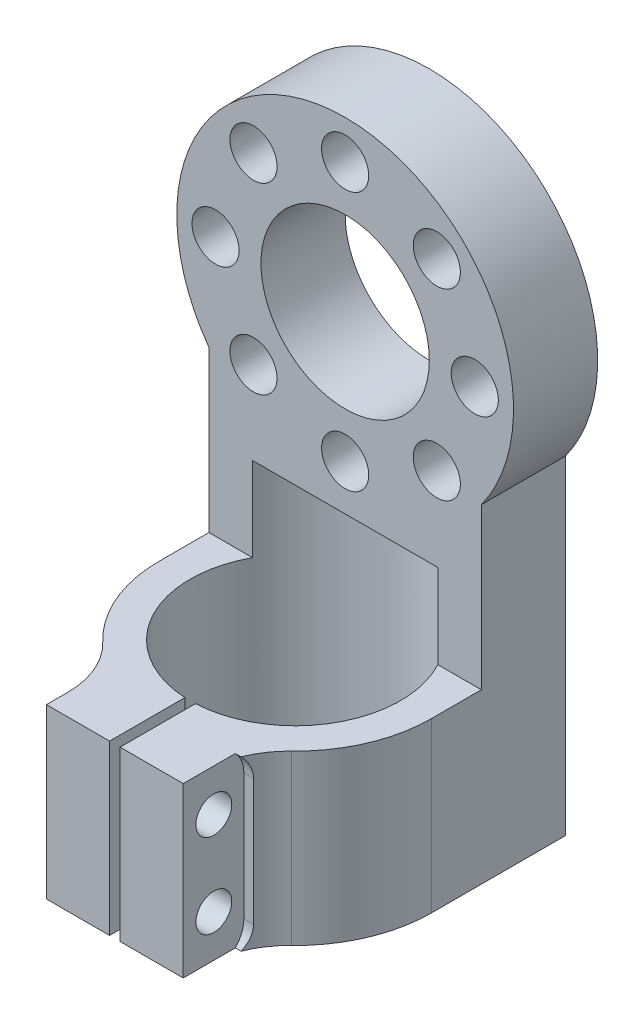
SolidWorks part; units mm, degrees
material "6061-T6 (SS)"
ref_plane "Plan de face" through (0, 0, 0) normal (0, 0, 1) x (1, 0, 0)
ref_plane "Plan de dessus" through (0, 0, 0) normal (0, 1, 0) x (1, 0, 0)
ref_plane "Plan de droite" through (0, 0, 0) normal (1, 0, 0) x (0, 0, -1)
sketch "Esquisse1" plane through (0, 0, 0) normal (0, 0, 1) x (1, 0, 0)
  line L0 (-10.2743, -7.4652) -> (-10.2743, -32.258)
  line L1 (-10.2743, -32.258) -> (10.2743, -32.258)
  line L2 (10.2743, -32.258) -> (10.2743, -7.4652)
  line L3 (0, 9.779) -> (0, 0) construction
  arc A0 (10.2743, -7.4652) -> (-10.2743, -7.4652) centre (0, 0) ccw
  circle A1 centre (0, 0) radius 6.35
  circle A2 centre (0, 9.779) radius 1.778
  circle A3 centre (0, 0) radius 9.779 construction
  circle A4 centre (6.9148, 6.9148) radius 1.778
  circle A5 centre (9.779, 0) radius 1.778
  circle A6 centre (6.9148, -6.9148) radius 1.778
  circle A7 centre (0, -9.779) radius 1.778
  circle A8 centre (-6.9148, -6.9148) radius 1.778
  circle A9 centre (-9.779, 0) radius 1.778
  circle A10 centre (-6.9148, 6.9148) radius 1.778
  point P27 (0, 0)
  dimension "D1" = 25.4
  dimension "D4" = 12.7
  dimension "D5" = 3.556
  dimension "D6" = 19.558
  dimension "D2" = 32.258
  dimension "D3" = 20.5486
  dimension "D7" = 8
extrude "Boss.-Extru.1" add sketch "Esquisse1" along normal blind 6.35
sketch "Esquisse2" plane through (0, -32.258, 0) normal (0, -1, 0) x (1, 0, 0)
  line L0 (0, 0) -> (0, 10.1092) construction
  line L1 (-10.2743, 0) -> (10.2743, 0) construction
  line L2 (-10.2743, 10.1092) -> (-10.2743, 6.35)
  line L3 (-10.2743, 6.35) -> (10.2743, 6.35)
  line L4 (10.2743, 6.35) -> (10.2743, 10.1092)
  line L5 (-5.1594, 18.9941) -> (-5.1594, 23.7236)
  line L6 (-5.1594, 23.7236) -> (5.1594, 23.7236)
  line L7 (5.1594, 23.7236) -> (5.1594, 18.9941)
  line L8 (0, 23.7236) -> (0, 10.1092) construction
  arc A0 (10.2743, 10.1092) -> (5.1594, 18.9941) centre (0, 10.1092) ccw
  arc A1 (-5.1594, 18.9941) -> (-10.2743, 10.1092) centre (0, 10.1092) ccw
  dimension "D1" = 10.1092
  dimension "D2" = 23.7236
  dimension "D3" = 10.3187
extrude "Boss.-Extru.2" add sketch "Esquisse2" against normal blind 12.7
sketch "Esquisse3" plane through (0, -32.258, 0) normal (0, -1, 0) x (1, 0, 0)
  line L0 (-0.3969, 18.0368) -> (-0.3969, 23.7236)
  line L1 (5.1594, 23.7236) -> (-5.1594, 23.7236) construction
  line L2 (-0.3969, 23.7236) -> (0.3969, 23.7236)
  line L3 (0.3969, 23.7236) -> (0.3969, 18.0368)
  arc A0 (-0.3969, 18.0368) -> (0.3969, 18.0368) centre (0, 10.1092) ccw
  arc A1 (-5.1594, 18.9941) -> (-10.2743, 10.1092) centre (0, 10.1092) ccw construction
  dimension "D1" = 15.875
  dimension "D2" = 0.7937
extrude "Enlèv. mat.-Extru.1" cut sketch "Esquisse3" against normal blind 19.05
fillet "Congé1" radius 6.35 2 edges at (5.1594, -25.908, 18.9941) (-5.1594, -25.908, 18.9941)
sketch "Esquisse4" plane through (5.1594, 0, 0) normal (1, 0, 0) x (0, 0, -1)
  line L0 (-21.4376, -21.1455) -> (-21.4376, -30.6705) construction
  line L2 (-19.1516, -21.1455) -> (-19.1516, -30.6705)
  line L3 (-23.7236, -21.1455) -> (-23.7236, -30.6705)
  line L4 (-23.7236, -19.558) -> (-23.7236, -32.258) construction
  line L5 (-21.4376, -21.1455) -> (-21.4376, -19.558) construction
  line L6 (-22.1051, -19.558) -> (-23.7236, -19.558) construction
  line L7 (-21.4376, -30.6705) -> (-21.4376, -32.258) construction
  line L8 (-22.1051, -32.258) -> (-23.7236, -32.258) construction
  arc A0 (-19.1516, -21.1455) -> (-23.7236, -21.1455) centre (-21.4376, -21.1455) ccw
  arc A1 (-23.7236, -30.6705) -> (-19.1516, -30.6705) centre (-21.4376, -30.6705) ccw
  point P4 (-21.4376, -25.908)
  dimension "D1" = 2.286
  dimension "D2" = 9.525
extrude "Enlèv. mat.-Extru.2" cut sketch "Esquisse4" along normal up to next
sketch "Esquisse5" plane through (5.1594, 0, 0) normal (1, 0, 0) x (0, 0, -1)
  line L0 (-21.4154, -22.733) -> (-21.4154, -29.083) construction
  line L1 (-23.7236, -19.558) -> (-23.7236, -32.258) construction
  line L2 (-23.7236, -25.908) -> (-21.4154, -25.908) construction
  circle A0 centre (-21.4154, -22.733) radius 1.3525
  circle A1 centre (-21.4154, -29.083) radius 1.3525
  dimension "D1" = 2.7051
  dimension "D2" = 2.3082
  dimension "D3" = 6.35
extrude "Enlèv. mat.-Extru.3" cut sketch "Esquisse5" against normal through all
